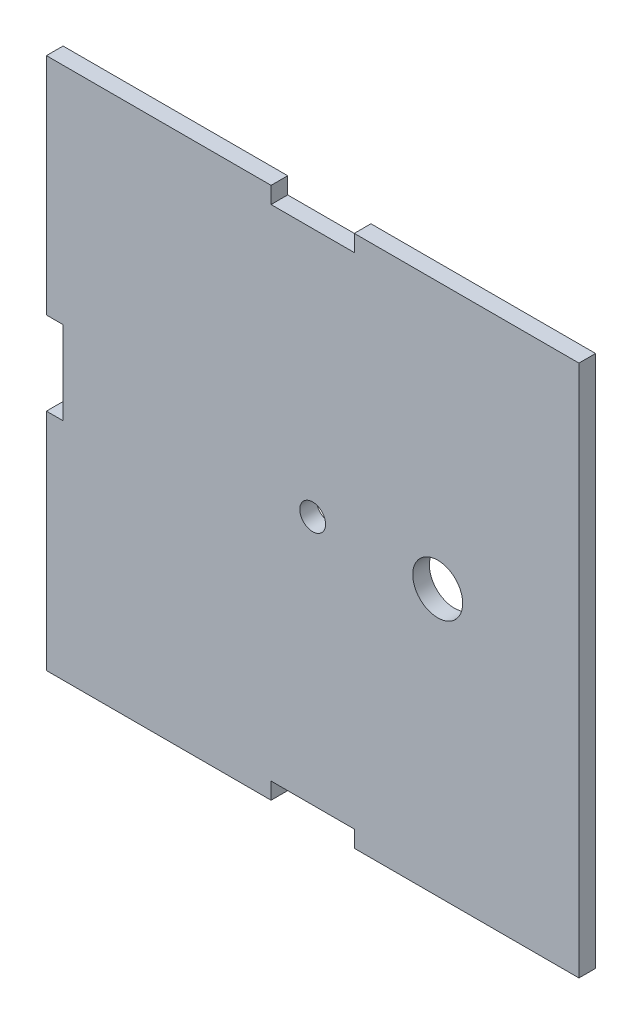
SolidWorks part; units mm, degrees
ref_plane "前视基准面" through (0, 0, 0) normal (0, 0, 1) x (1, 0, 0)
ref_plane "上视基准面" through (0, 0, 0) normal (0, 1, 0) x (1, 0, 0)
ref_plane "右视基准面" through (0, 0, 0) normal (1, 0, 0) x (0, 0, -1)
sketch "草图1" plane through (0, 0, 0) normal (0, 0, 1) x (1, 0, 0)
  line L0 (16.9744, 42.2051) -> (2.9744, 42.2051)
  line L1 (16.9744, 42.2051) -> (-10.0256, 42.2051)
  line L2 (16.9744, 42.2051) -> (16.9744, 15.2051)
  line L3 (16.9744, -21.7949) -> (-10.0256, -21.7949)
  line L4 (-47.0256, 42.2051) -> (-47.0256, 15.2051)
  line L5 (2.9744, 42.2051) -> (-5.2982, 42.2051)
  line L7 (-10.0256, 42.2051) -> (-10.0256, 40.2051)
  line L8 (-10.0256, 40.2051) -> (-20.0256, 40.2051)
  line L9 (-20.0256, 40.2051) -> (-20.0256, 42.2051)
  line L10 (-10.0256, -21.7949) -> (-10.0256, -19.7949)
  line L11 (-10.0256, -19.7949) -> (-20.0256, -19.7949)
  line L12 (-20.0256, -19.7949) -> (-20.0256, -21.7949)
  line L13 (-20.0256, -21.7949) -> (-47.0256, -21.7949)
  line L14 (-47.0256, 15.2051) -> (-45.0256, 15.2051)
  line L15 (-45.0256, 15.2051) -> (-45.0256, 5.2051)
  line L16 (-45.0256, 5.2051) -> (-47.0256, 5.2051)
  line L20 (-20.0256, 42.2051) -> (-47.0256, 42.2051)
  line L21 (-47.0256, 5.2051) -> (-47.0256, -21.7949)
  line L22 (16.9744, 5.2051) -> (16.9744, -21.7949)
  line L23 (16.9744, 5.2051) -> (16.9744, 15.2051)
  point P9 (-15.0256, 42.2051)
  dimension "D1" = 64
  dimension "D2" = 64
  dimension "D3" = 14
  dimension "D4" = 64
extrude "凸台-拉伸1" add sketch "草图1" along normal blind 2
sketch "草图2" plane through (0, 0, 0) normal (0, 0, 1) x (1, 0, 0)
  line L0 (-47.0256, 10.2051) -> (29.7062, 10.2051) construction
  line L1 (-47.0256, 5.2051) -> (-47.0256, 15.2051) construction
  line L2 (-15.0256, 42.2051) -> (-15.0256, -23.8535) construction
  line L3 (-10.0256, 42.2051) -> (-20.0256, 42.2051) construction
  circle A0 centre (-15.0256, 10.2051) radius 1.55
extrude "切除-拉伸1" cut sketch "草图2" along normal blind 5
sketch "草图3" plane through (0, 0, 2) normal (0, 0, 1) x (1, 0, 0)
  circle A0 centre (0, 10.2051) radius 3
extrude "切除-拉伸2" cut sketch "草图3" against normal blind 10
